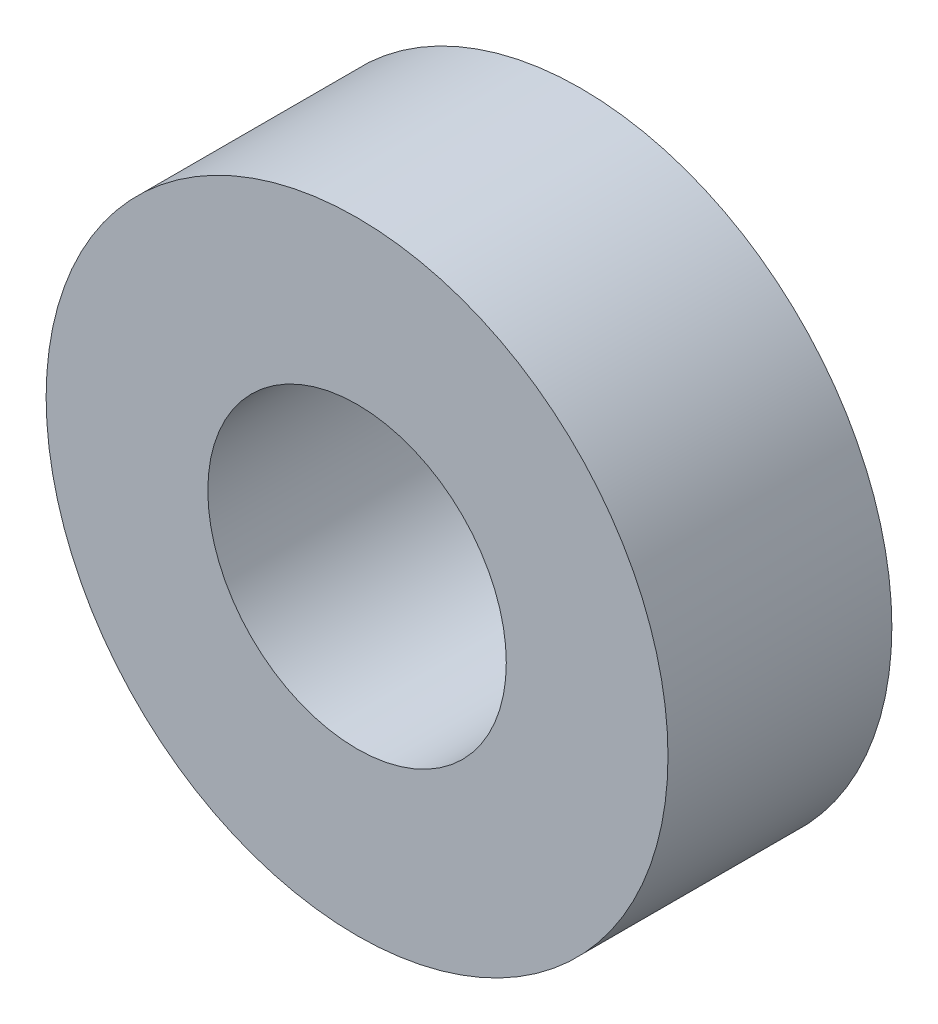
SolidWorks part; units mm, degrees
material "VITON"
ref_plane "Front Plane" through (0, 0, 0) normal (0, 0, 1) x (1, 0, 0)
ref_plane "Top Plane" through (0, 0, 0) normal (0, 1, 0) x (1, 0, 0)
ref_plane "Right Plane" through (0, 0, 0) normal (1, 0, 0) x (0, 0, -1)
sketch "BaseS" plane through (0, 0, 0) normal (0, 0, 1) x (1, 0, 0)
  circle A0 centre (0, 0) radius 6.25
  circle A1 centre (0, 0) radius 3
  dimension "D1" = 12.5
  dimension "D2" = 3.25
  dimension "D3" = 6
extrude "BASE" add sketch "BaseS" along normal blind 4.5
